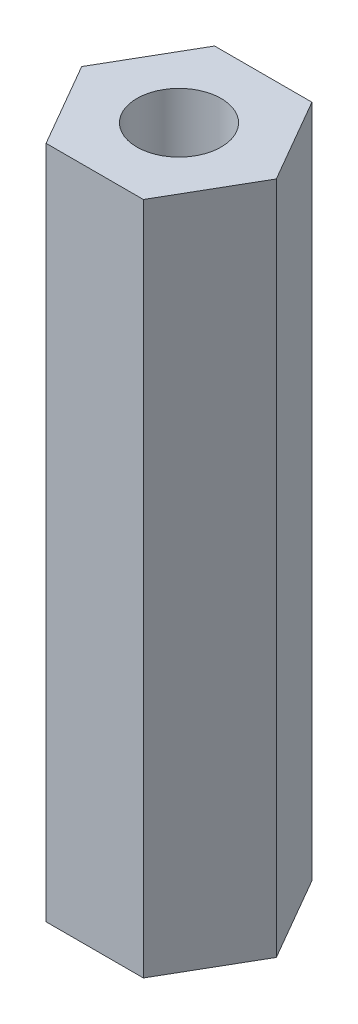
SolidWorks part; units mm, degrees
ref_plane "Front Plane" through (0, 0, 0) normal (0, 0, 1) x (1, 0, 0)
ref_plane "Top Plane" through (0, 0, 0) normal (0, 1, 0) x (1, 0, 0)
ref_plane "Right Plane" through (0, 0, 0) normal (1, 0, 0) x (0, 0, -1)
sketch "Sketch1" plane through (0, 0, 0) normal (0, 1, 0) x (1, 0, 0)
  line L1 (7.3323, 0) -> (3.6662, 6.35)
  line L2 (3.6662, 6.35) -> (-3.6662, 6.35)
  line L3 (-3.6662, 6.35) -> (-7.3323, 0)
  line L4 (-7.3323, 0) -> (-3.6662, -6.35)
  line L5 (-3.6662, -6.35) -> (3.6662, -6.35)
  line L6 (3.6662, -6.35) -> (7.3323, 0)
  circle A1 centre (0, 0) radius 3.175
  circle A2 centre (0, 0) radius 6.35 construction
extrude "Boss-Extrude1" add sketch "Sketch1" along normal blind 50.8
